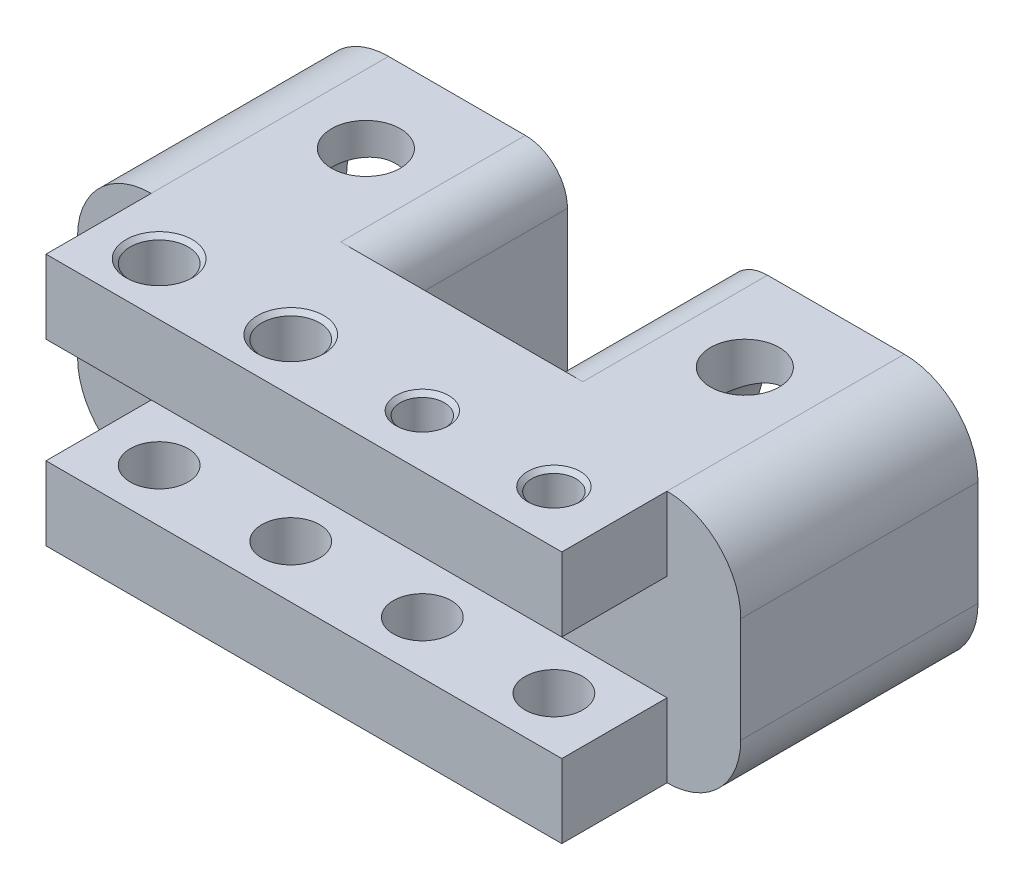
SolidWorks part; units mm, degrees
material "6061-T6 (SS)"
ref_plane "Front Plane" through (0, 0, 0) normal (0, 0, 1) x (1, 0, 0)
ref_plane "Top Plane" through (0, 0, 0) normal (0, 1, 0) x (1, 0, 0)
ref_plane "Right Plane" through (0, 0, 0) normal (1, 0, 0) x (0, 0, -1)
ref_plane "Plane1" through (0, 0, 5) normal (0, 0, 1) x (1, 0, 0)
sketch "Sketch1" plane through (0, 0, 5) normal (0, 0, 1) x (1, 0, 0)
  line L0 (-12, 12) -> (-12, -12)
  line L1 (-12, -12) -> (51, -12)
  line L2 (51, -12) -> (51, 12)
  line L3 (51, 12) -> (-12, 12)
extrude "Boss-Extrude1" add sketch "Sketch1" against normal blind 20
sketch "Sketch2" plane through (0, -12, 0) normal (0, -1, 0) x (1, 0, 0)
  line L0 (12, -15) -> (27, -15)
  line L1 (27, -15) -> (27, 0)
  line L2 (27, 0) -> (12, 0)
  line L3 (12, 0) -> (12, -15)
extrude "Cut-Extrude1" cut sketch "Sketch2" against normal through all
sketch "Sketch3" plane through (0, 0, 5) normal (0, 0, 1) x (1, 0, 0)
  line L0 (-5, -12) -> (-5, -5)
  line L1 (-5, -5) -> (44, -5)
  line L2 (44, -5) -> (44, -12)
  line L3 (44, -12) -> (-5, -12)
extrude "Boss-Extrude2" add sketch "Sketch3" along normal blind 10
sketch "Sketch4" plane through (0, 0, 5) normal (0, 0, 1) x (1, 0, 0)
  line L0 (44, 12) -> (44, 5)
  line L1 (44, 5) -> (-5, 5)
  line L2 (-5, 5) -> (-5, 12)
  line L3 (-5, 12) -> (44, 12)
extrude "Boss-Extrude3" add sketch "Sketch4" along normal blind 10
hole_wizard "Hole1" positions "Sketch6" profile "Sketch5" legacy
sketch "Sketch6" plane through (0, 0, -15) normal (0, 0, -1) x (-1, 0, 0)
  point P0 (0, 0)
  point P1 (-39, 0)
sketch "Sketch5" plane through (0, 0, -15) normal (1, 0, 0) x (0, 1, 0)
  line L0 (0, 0) -> (0, 15)
  line L1 (0, 15) -> (9, 15)
  line L2 (9, 15) -> (9, 0)
  line L3 (9, 0) -> (0, 0)
  line L4 (0, 110) -> (0, -10) construction
  dimension "Diameter" = 18
  dimension "Depth" = 15
hole_wizard "#6 Clearance Hole1" positions "Sketch8" profile "Sketch7" hole size "#6" standard "ANSI Inch"
sketch "Sketch8" plane through (0, 5, 0) normal (0, -1, 0) x (-1, 0, 0)
  point P0 (-0.75, -10)
sketch "Sketch7" plane through (0.75, 5, 10) normal (1, 0, 0) x (0, 0, -1)
  line L0 (0, 0) -> (0, 7)
  line L1 (0, 7) -> (2.1, 7)
  line L2 (2.1, 7) -> (2.1, 0)
  line L5 (2.1, 0) -> (0, 0)
  line L11 (0, -6.35) -> (0, 107.95) construction
  dimension "Thru Hole Dia." = 4.2
  dimension "Thru Hole Depth" = 7
hole_wizard "#6 Clearance Hole2" positions "Sketch10" profile "Sketch9" hole size "#6" standard "ANSI Inch"
sketch "Sketch10" plane through (0, 12, 0) normal (0, 1, 0) x (1, 0, 0)
  point P0 (38.25, -10)
  point P1 (25.75, -10)
  point P2 (13.25, -10)
sketch "Sketch9" plane through (38.25, 12, 10) normal (1, 0, 0) x (0, 0, 1)
  line L0 (0, 0) -> (0, 7)
  line L1 (0, 7) -> (2.1, 7)
  line L2 (2.1, 7) -> (2.1, 0)
  line L5 (2.1, 0) -> (0, 0)
  line L11 (0, -6.35) -> (0, 107.95) construction
  dimension "Thru Hole Dia." = 4.2
  dimension "Thru Hole Depth" = 7
hole_wizard "#10 Clearance Hole1" positions "Sketch12" profile "Sketch11" hole size "#10" standard "ANSI Inch"
sketch "Sketch12" plane through (0, -12, 0) normal (0, -1, 0) x (-1, 0, 0)
  point P0 (-13.25, -10)
  point P1 (-0.75, -10)
sketch "Sketch11" plane through (13.25, -12, 10) normal (1, 0, 0) x (0, 0, -1)
  line L0 (0, 0) -> (0, 24)
  line L1 (0, 24) -> (2.75, 24)
  line L2 (2.75, 24) -> (2.75, 0)
  line L5 (2.75, 0) -> (0, 0)
  line L11 (0, -6.35) -> (0, 107.95) construction
  dimension "Thru Hole Dia." = 5.5
  dimension "Thru Hole Depth" = 24
hole_wizard "#10 Clearance Hole2" positions "Sketch14" profile "Sketch13" hole size "#10" standard "ANSI Inch"
sketch "Sketch14" plane through (0, -5, 0) normal (0, 1, 0) x (1, 0, 0)
  point P0 (38.25, -10)
  point P1 (25.75, -10)
sketch "Sketch13" plane through (38.25, -5, 10) normal (1, 0, 0) x (0, 0, 1)
  line L0 (0, 0) -> (0, 7)
  line L1 (0, 7) -> (2.75, 7)
  line L2 (2.75, 7) -> (2.75, 0)
  line L5 (2.75, 0) -> (0, 0)
  line L11 (0, -6.35) -> (0, 107.95) construction
  dimension "Thru Hole Dia." = 5.5
  dimension "Thru Hole Depth" = 7
chamfer "Chamfer1" distance 0.4 angle 45 8 edges at (25.75, -12, 12.75) (38.25, -12, 12.75) (38.25, 12, 12.1) (25.75, 12, 12.1) (13.25, -12, 7.25) (0.75, -12, 7.25) (0.75, 12, 7.25) (13.25, 12, 7.25)
fillet "Fillet1" radius 4 4 edges at (12, 12, -7.5) (12, -12, -7.5) (27, -12, -7.5) (27, 12, -7.5)
fillet "Fillet2" radius 7 4 edges at (51, -12, -5) (-12, 12, -5) (51, 12, -5) (-12, -12, -5)
sketch "Sketch20" plane through (0, 0, -15) normal (0, 0, -1) x (-1, 0, 0)
  line L0 (12, -5) -> (12, 5) construction
  line L1 (5, 12) -> (-8, 12) construction
  line L2 (-12, 8) -> (-12, -8) construction
  line L3 (-8, -12) -> (5, -12) construction
  line L4 (-51, 5) -> (-51, -5) construction
  line L5 (-44, -12) -> (-31, -12) construction
  line L6 (-27, -8) -> (-27, 8) construction
  line L7 (-31, 12) -> (-44, 12) construction
  line L8 (12, -5) -> (12, 5)
  line L9 (5, 12) -> (-8, 12)
  line L10 (-12, 8) -> (-12, -8)
  line L11 (-8, -12) -> (5, -12)
  line L12 (-51, 5) -> (-51, -5)
  line L13 (-44, -12) -> (-31, -12)
  line L14 (-27, -8) -> (-27, 8)
  line L15 (-31, 12) -> (-44, 12)
  arc A0 (12, 5) -> (5, 12) centre (5, 5) ccw construction
  arc A1 (-8, 12) -> (-12, 8) centre (-8, 8) ccw construction
  arc A2 (-12, -8) -> (-8, -12) centre (-8, -8) ccw construction
  arc A3 (5, -12) -> (12, -5) centre (5, -5) ccw construction
  arc A4 (-51, -5) -> (-44, -12) centre (-44, -5) ccw construction
  arc A5 (-31, -12) -> (-27, -8) centre (-31, -8) ccw construction
  arc A6 (-27, 8) -> (-31, 12) centre (-31, 8) ccw construction
  arc A7 (-44, 12) -> (-51, 5) centre (-44, 5) ccw construction
  arc A8 (12, 5) -> (5, 12) centre (5, 5) ccw
  arc A9 (-8, 12) -> (-12, 8) centre (-8, 8) ccw
  arc A10 (-12, -8) -> (-8, -12) centre (-8, -8) ccw
  arc A11 (5, -12) -> (12, -5) centre (5, -5) ccw
  arc A12 (-51, -5) -> (-44, -12) centre (-44, -5) ccw
  arc A13 (-31, -12) -> (-27, -8) centre (-31, -8) ccw
  arc A14 (-27, 8) -> (-31, 12) centre (-31, 8) ccw
  arc A15 (-44, 12) -> (-51, 5) centre (-44, 5) ccw
  circle A16 centre (0, 0) radius 9 construction
  circle A17 centre (-39, 0) radius 9 construction
  circle A18 centre (0, 0) radius 9
  circle A19 centre (-39, 0) radius 9
extrude "Boss-Extrude5" add sketch "Sketch20" along normal blind 2.54
sketch "Sketch21" plane through (0, 12, 0) normal (0, 1, 0) x (1, 0, 0)
  line L0 (37.5, 10.795) -> (37.5, 6.985) construction
  line L3 (48, 0) -> (30, 0) construction
  line L4 (19.5, 0) -> (19.5, 21.8278) construction
  line L5 (31, 0) -> (8, 0) construction
  line L6 (1.5, 10.795) -> (1.5, 6.985) construction
  circle A4 centre (37.5, 8.89) radius 3.2639
  circle A5 centre (1.5, 8.89) radius 3.2639
  point P2 (37.5, 8.89)
  point P15 (1.5, 8.89)
  dimension "D1" = 8.89
  dimension "D3" = 3.81
extrude "Cut-Extrude4" cut sketch "Sketch21" against normal through all
